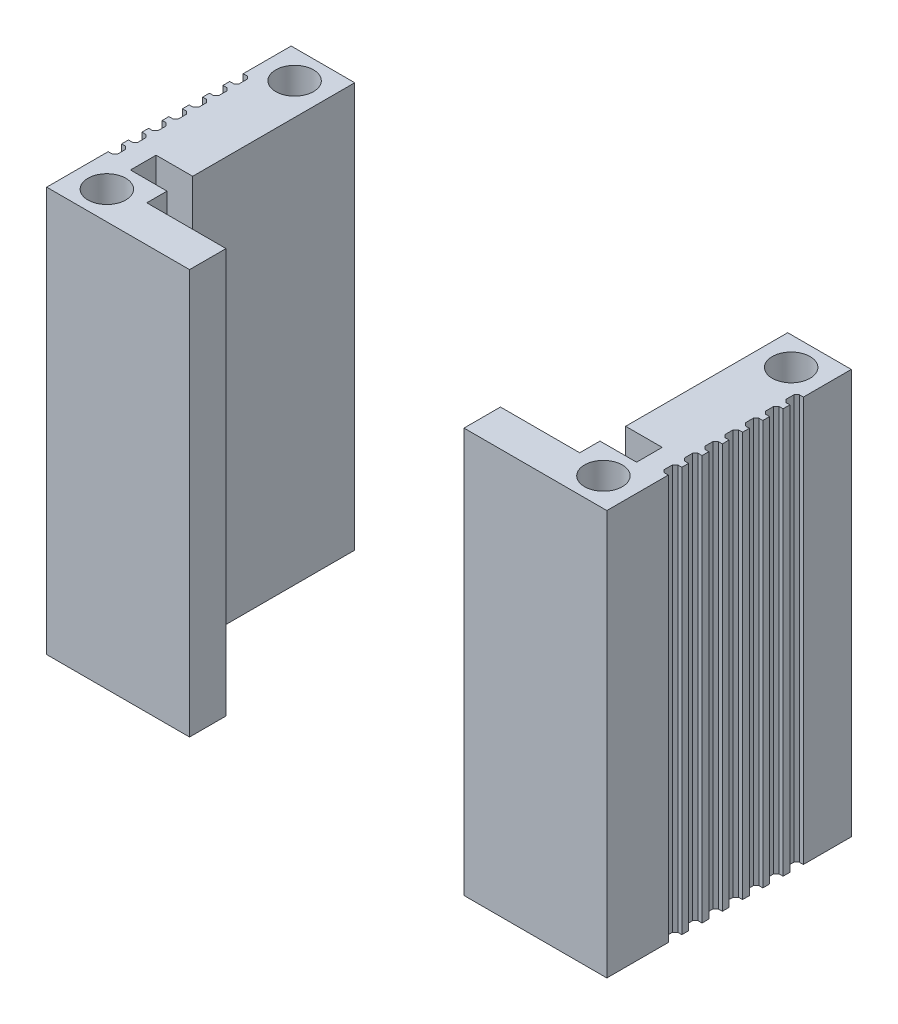
SolidWorks part; units mm, degrees
ref_plane "前视基准面" through (0, 0, 0) normal (0, 0, 1) x (1, 0, 0)
ref_plane "上视基准面" through (0, 0, 0) normal (0, 1, 0) x (1, 0, 0)
ref_plane "右视基准面" through (0, 0, 0) normal (1, 0, 0) x (0, 0, -1)
sketch "草图1" plane through (0, 0, 0) normal (0, 0, 1) x (1, 0, 0)
  line L4 (18.7373, -9.5383) -> (18.7373, 20.4363)
  line L5 (18.7373, 20.4363) -> (-18.7373, 20.4363)
  line L6 (-18.7373, 20.4363) -> (-18.7373, -9.5383)
  line L7 (-18.7373, -9.5383) -> (18.7373, -9.5383)
  line L8 (18.7373, -9.5383) -> (18.7373, 20.4363)
  line L9 (18.7373, 20.4363) -> (-18.7373, 20.4363)
  line L10 (-18.7373, 20.4363) -> (-18.7373, -9.5383)
  line L11 (-18.7373, -9.5383) -> (18.7373, -9.5383)
  dimension "D1" = 0
extrude "凸台-拉伸1" add sketch "草图1" along normal blind 3
sketch "草图2" plane through (-18.7373, 0, 0) normal (-1, 0, 0) x (0, 0, 1)
  line L4 (0, 20.4363) -> (0, -9.5383)
  line L5 (0, -9.5383) -> (3, -9.5383)
  line L6 (3, -9.5383) -> (3, 20.4363)
  line L7 (3, 20.4363) -> (0, 20.4363)
  line L8 (0, 20.4363) -> (0, -9.5383)
  line L9 (0, -9.5383) -> (3, -9.5383)
  line L10 (3, -9.5383) -> (3, 20.4363)
  line L11 (3, 20.4363) -> (0, 20.4363)
  dimension "D1" = 0
extrude "凸台-拉伸2" add sketch "草图2" along normal blind 3
sketch "草图3" plane through (18.7373, 0, 0) normal (1, 0, 0) x (0, 0, -1)
  line L4 (0, -9.5383) -> (0, 20.4363)
  line L5 (0, 20.4363) -> (-3, 20.4363)
  line L6 (-3, 20.4363) -> (-3, -9.5383)
  line L7 (-3, -9.5383) -> (0, -9.5383)
  line L8 (0, -9.5383) -> (0, 20.4363)
  line L9 (0, 20.4363) -> (-3, 20.4363)
  line L10 (-3, 20.4363) -> (-3, -9.5383)
  line L11 (-3, -9.5383) -> (0, -9.5383)
  dimension "D1" = 0
extrude "凸台-拉伸3" add sketch "草图3" along normal blind 3
sketch "草图4" plane through (0, 0, 0) normal (0, 0, -1) x (-1, 0, 0)
  line L0 (-18.7373, -9.5383) -> (-18.7373, 20.4363) construction
  line L1 (-18.7373, -9.5383) -> (-18.7373, 20.4363)
  line L2 (18.7373, 20.4363) -> (18.7373, -9.5383) construction
  line L3 (18.7373, 20.4363) -> (18.7373, -9.5383)
  line L4 (-18.7373, 20.4363) -> (-21.7373, 20.4363)
  line L5 (18.7373, -9.5383) -> (21.7373, -9.5383)
  line L8 (-21.7373, -9.5383) -> (21.7373, -9.5383)
  line L9 (-21.7373, 20.4363) -> (-21.7373, -9.5383)
  line L10 (21.7373, 20.4363) -> (-21.7373, 20.4363)
  line L11 (21.7373, -9.5383) -> (21.7373, 20.4363)
  line L12 (-21.7373, -9.5383) -> (-18.7373, -9.5383)
  line L13 (-21.7373, 20.4363) -> (-21.7373, -9.5383)
  line L14 (21.7373, 20.4363) -> (18.7373, 20.4363)
  line L15 (21.7373, -9.5383) -> (21.7373, 20.4363)
  dimension "D1" = 0
extrude "凸台-拉伸4" add sketch "草图4" along normal blind 1.6 contours L12 L1 L4 L13 | L14 L3 L5 L15
sketch "草图5" plane through (0, 0, -1.6) normal (0, 0, -1) x (-1, 0, 0)
  line L0 (-18.7373, -9.5383) -> (-16.0288, -9.5383)
  line L1 (18.7373, -9.5383) -> (-18.7373, -9.5383) construction
  line L2 (-16.0288, -9.5383) -> (-16.0288, 20.4363)
  line L3 (-18.7373, 20.4363) -> (-16.0288, 20.4363)
  line L4 (-21.7373, 20.4363) -> (-21.7373, -9.5383)
  line L5 (-21.7373, -9.5383) -> (-18.7373, -9.5383)
  line L6 (-18.7373, -9.5383) -> (-18.7373, 20.4363)
  line L7 (-18.7373, 20.4363) -> (-21.7373, 20.4363)
  line L8 (-21.7373, 20.4363) -> (-21.7373, -9.5383)
  line L9 (-21.7373, -9.5383) -> (-18.7373, -9.5383)
  line L11 (-18.7373, 20.4363) -> (-21.7373, 20.4363)
  line L12 (18.7373, 20.4363) -> (21.7373, 20.4363)
  line L22 (21.7373, -9.5383) -> (18.7373, -9.5383)
  line L23 (21.7373, 20.4363) -> (21.7373, -9.5383)
  line L24 (18.7373, 20.4363) -> (16.0288, 20.4363)
  line L25 (16.0288, -9.5383) -> (16.0288, 20.4363)
  line L26 (18.7373, -9.5383) -> (16.0288, -9.5383)
  dimension "D1" = 0
extrude "凸台-拉伸7" add sketch "草图5" along normal up to vertex (1.6 mm away) contours L8 L9 L0 L2 L3 L11 | L12 L23 L22 L26 L25 L24
sketch "草图7" plane through (0, 0, 0) normal (0, 0, -1) x (-1, 0, 0)
  line L4 (18.7373, -9.5383) -> (18.7373, 20.4363)
  line L5 (18.7373, 20.4363) -> (-18.7373, 20.4363)
  line L6 (-18.7373, 20.4363) -> (-18.7373, -9.5383)
  line L7 (-18.7373, -9.5383) -> (18.7373, -9.5383)
  line L8 (18.7373, -9.5383) -> (18.7373, 20.4363)
  line L9 (18.7373, 20.4363) -> (-18.7373, 20.4363)
  line L10 (-18.7373, 20.4363) -> (-18.7373, -9.5383)
  line L11 (-18.7373, -9.5383) -> (18.7373, -9.5383)
  dimension "D1" = 0
extrude "切除-拉伸1" cut sketch "草图7" against normal blind 0.3
sketch "草图8" plane through (0, 0, 3) normal (0, 0, 1) x (1, 0, 0)
  line L1 (-10.16, 19.648) -> (-10.16, 17.408) construction
  line L2 (-10.16, 20.4363) -> (-10.16, -9.5383)
  line L3 (10.16, 17.408) -> (10.16, 19.648) construction
  line L4 (-21.7373, -9.5383) -> (21.7373, -9.5383)
  line L5 (21.7373, -9.5383) -> (21.7373, 20.4363)
  line L6 (21.7373, 20.4363) -> (-21.7373, 20.4363)
  line L7 (-21.7373, 20.4363) -> (-21.7373, -9.5383)
  line L8 (-10.16, -9.5383) -> (10.16, -9.5383)
  line L10 (10.16, 20.4363) -> (-10.16, 20.4363)
  line L12 (10.16, -9.5383) -> (10.16, 20.4363)
  dimension "D1" = 0
extrude "切除-拉伸3" cut sketch "草图8" against normal up to surface (2.7 mm away) contours L8 L12 L10 L2 up to face at (0, 5.449, 0.3)
sketch "草图9" plane through (0, 0, 0.3) normal (0, 0, -1) x (-1, 0, 0)
  line L0 (16.0288, -9.5383) -> (16.0288, 20.4363) construction
  line L1 (16.0288, -9.5383) -> (16.0288, 20.4363)
  line L2 (-16.0288, -9.5383) -> (-16.0288, 20.4363) construction
  line L3 (-16.0288, -9.5383) -> (-16.0288, 20.4363)
  line L8 (10.16, 20.4363) -> (10.16, -9.5383)
  line L9 (10.16, -9.5383) -> (18.7373, -9.5383)
  line L10 (18.7373, -9.5383) -> (18.7373, 20.4363)
  line L11 (18.7373, 20.4363) -> (10.16, 20.4363)
  line L12 (10.16, 20.4363) -> (10.16, -9.5383)
  line L13 (10.16, -9.5383) -> (16.0288, -9.5383)
  line L15 (16.0288, 20.4363) -> (10.16, 20.4363)
  line L16 (-10.16, -9.5383) -> (-10.16, 20.4363)
  line L17 (-10.16, 20.4363) -> (-18.7373, 20.4363)
  line L18 (-18.7373, 20.4363) -> (-18.7373, -9.5383)
  line L19 (-18.7373, -9.5383) -> (-10.16, -9.5383)
  line L20 (-10.16, -9.5383) -> (-10.16, 20.4363)
  line L21 (-10.16, 20.4363) -> (-16.0288, 20.4363)
  line L23 (-16.0288, -9.5383) -> (-10.16, -9.5383)
  dimension "D1" = 0
  dimension "D2" = 0
extrude "切除-拉伸4" cut sketch "草图9" against normal blind 1.5
sketch "草图10" plane through (0, 0, 3) normal (0, 0, 1) x (1, 0, 0)
  line L4 (-10.16, -9.5383) -> (-10.16, 20.4363)
  line L5 (-10.16, 20.4363) -> (-21.7373, 20.4363)
  line L6 (-21.7373, 20.4363) -> (-21.7373, -9.5383)
  line L7 (-21.7373, -9.5383) -> (-10.16, -9.5383)
  line L8 (-10.16, -9.5383) -> (-10.16, 20.4363)
  line L9 (-10.16, 20.4363) -> (-21.7373, 20.4363)
  line L10 (-21.7373, 20.4363) -> (-21.7373, -9.5383)
  line L11 (-21.7373, -9.5383) -> (-10.16, -9.5383)
  line L12 (10.16, 20.4363) -> (10.16, -9.5383)
  line L13 (10.16, -9.5383) -> (21.7373, -9.5383)
  line L14 (21.7373, -9.5383) -> (21.7373, 20.4363)
  line L15 (21.7373, 20.4363) -> (10.16, 20.4363)
  line L16 (10.16, 20.4363) -> (10.16, -9.5383)
  line L17 (10.16, -9.5383) -> (21.7373, -9.5383)
  line L18 (21.7373, -9.5383) -> (21.7373, 20.4363)
  line L19 (21.7373, 20.4363) -> (10.16, 20.4363)
  dimension "D1" = 0
  dimension "D2" = 0
extrude "凸台-拉伸8" add sketch "草图10" along normal blind 1.5
sketch "草图11" plane through (21.7373, 0, 0) normal (1, 0, 0) x (0, 0, -1)
  line L4 (-4.5, -9.5383) -> (13.6, -9.5383)
  line L5 (13.6, -9.5383) -> (13.6, 20.4363)
  line L6 (13.6, 20.4363) -> (-4.5, 20.4363)
  line L7 (-4.5, 20.4363) -> (-4.5, -9.5383)
  line L8 (-4.5, -9.5383) -> (13.6, -9.5383)
  line L9 (13.6, -9.5383) -> (13.6, 20.4363)
  line L10 (13.6, 20.4363) -> (-4.5, 20.4363)
  line L11 (-4.5, 20.4363) -> (-4.5, -9.5383)
  dimension "D1" = 0
extrude "切除-拉伸5" cut sketch "草图11" against normal blind 1
sketch "草图12" plane through (-21.7373, 0, 0) normal (-1, 0, 0) x (0, 0, 1)
  line L4 (4.5, 20.4363) -> (-13.6, 20.4363)
  line L5 (-13.6, 20.4363) -> (-13.6, -9.5383)
  line L6 (-13.6, -9.5383) -> (4.5, -9.5383)
  line L7 (4.5, -9.5383) -> (4.5, 20.4363)
  line L8 (4.5, 20.4363) -> (-13.6, 20.4363)
  line L9 (-13.6, 20.4363) -> (-13.6, -9.5383)
  line L10 (-13.6, -9.5383) -> (4.5, -9.5383)
  line L11 (4.5, -9.5383) -> (4.5, 20.4363)
  dimension "D1" = 0
extrude "切除-拉伸6" cut sketch "草图12" against normal blind 1
sketch "草图14" plane through (0, -9.5383, 0) normal (0, -1, 0) x (1, 0, 0)
  circle A0 centre (18.3831, -11.5) radius 1.4 construction
  circle A1 centre (18.3831, -11.5) radius 1.4
  circle A2 centre (18.3831, 2.4) radius 1.4 construction
  circle A3 centre (18.3831, 2.4) radius 1.4
  circle A4 centre (-18.3831, 2.4) radius 1.4 construction
  circle A5 centre (-18.3831, 2.4) radius 1.4
  circle A6 centre (-18.3831, -11.5) radius 1.4 construction
  circle A7 centre (-18.3831, -11.5) radius 1.4
extrude "切除-拉伸7" cut sketch "草图14" against normal up to next
sketch "草图16" plane through (0, -9.5383, 0) normal (0, -1, 0) x (1, 0, 0)
  line L0 (-20.7373, -4.55) -> (-20.2373, -4.55)
  line L1 (-20.7373, -13.6) -> (-20.7373, 4.5) construction
  line L2 (-20.7373, -6.05) -> (-20.2373, -6.05)
  line L3 (-20.7373, -4.55) -> (-20.7373, -5.55)
  line L4 (-20.7373, -5.55) -> (-20.2373, -5.55)
  line L5 (-20.7373, -6.05) -> (-20.7373, -7.05)
  line L6 (-20.7373, -5.55) -> (-20.2373, -5.55)
  line L7 (-20.2373, -5.55) -> (-20.2373, -4.55)
  line L8 (-20.7373, -7.05) -> (-20.2373, -7.05)
  line L9 (-20.7373, -7.05) -> (-20.2373, -7.05)
  line L10 (-20.2373, -7.05) -> (-20.2373, -6.05)
  line L11 (-20.7373, -7.55) -> (-20.2373, -7.55)
  line L12 (-20.7373, -7.55) -> (-20.7373, -8.55)
  line L13 (-20.7373, -8.55) -> (-20.2373, -8.55)
  line L14 (-20.7373, -8.55) -> (-20.2373, -8.55)
  line L15 (-20.2373, -8.55) -> (-20.2373, -7.55)
  line L16 (-20.7373, -9.05) -> (-20.2373, -9.05)
  line L17 (-20.7373, -9.05) -> (-20.7373, -10.05)
  line L18 (-20.7373, -10.05) -> (-20.2373, -10.05)
  line L19 (-20.7373, -10.05) -> (-20.2373, -10.05)
  line L20 (-20.2373, -10.05) -> (-20.2373, -9.05)
  line L21 (-20.7373, -3.05) -> (-20.2373, -3.05)
  line L22 (-20.7373, -3.05) -> (-20.7373, -4.05)
  line L23 (-20.7373, -4.05) -> (-20.2373, -4.05)
  line L24 (-20.7373, -4.05) -> (-20.2373, -4.05)
  line L25 (-20.2373, -4.05) -> (-20.2373, -3.05)
  line L26 (-20.7373, -1.55) -> (-20.2373, -1.55)
  line L27 (-20.7373, -1.55) -> (-20.7373, -2.55)
  line L28 (-20.7373, -2.55) -> (-20.2373, -2.55)
  line L29 (-20.7373, -2.55) -> (-20.2373, -2.55)
  line L30 (-20.2373, -2.55) -> (-20.2373, -1.55)
  line L31 (-20.7373, -0.05) -> (-20.2373, -0.05)
  line L32 (-20.7373, -0.05) -> (-20.7373, -1.05)
  line L33 (-20.7373, -1.05) -> (-20.2373, -1.05)
  line L34 (-20.7373, -1.05) -> (-20.2373, -1.05)
  line L35 (-20.2373, -1.05) -> (-20.2373, -0.05)
  line L38 (20.2373, -1.05) -> (20.2373, -0.05)
  line L39 (20.7373, -1.05) -> (20.2373, -1.05)
  line L40 (20.7373, -1.05) -> (20.2373, -1.05)
  line L41 (20.7373, -0.05) -> (20.7373, -1.05)
  line L42 (20.7373, -0.05) -> (20.2373, -0.05)
  line L43 (20.2373, -2.55) -> (20.2373, -1.55)
  line L44 (20.7373, -2.55) -> (20.2373, -2.55)
  line L45 (20.7373, -2.55) -> (20.2373, -2.55)
  line L46 (20.7373, -1.55) -> (20.7373, -2.55)
  line L47 (20.7373, -1.55) -> (20.2373, -1.55)
  line L48 (20.2373, -4.05) -> (20.2373, -3.05)
  line L49 (20.7373, -4.05) -> (20.2373, -4.05)
  line L50 (20.7373, -4.05) -> (20.2373, -4.05)
  line L51 (20.7373, -3.05) -> (20.7373, -4.05)
  line L52 (20.7373, -3.05) -> (20.2373, -3.05)
  line L53 (20.2373, -10.05) -> (20.2373, -9.05)
  line L54 (20.7373, -10.05) -> (20.2373, -10.05)
  line L55 (20.7373, -10.05) -> (20.2373, -10.05)
  line L56 (20.7373, -9.05) -> (20.7373, -10.05)
  line L57 (20.7373, -9.05) -> (20.2373, -9.05)
  line L58 (20.2373, -8.55) -> (20.2373, -7.55)
  line L59 (20.7373, -8.55) -> (20.2373, -8.55)
  line L60 (20.7373, -8.55) -> (20.2373, -8.55)
  line L61 (20.7373, -7.55) -> (20.7373, -8.55)
  line L62 (20.7373, -7.55) -> (20.2373, -7.55)
  line L63 (20.2373, -7.05) -> (20.2373, -6.05)
  line L64 (20.7373, -7.05) -> (20.2373, -7.05)
  line L65 (20.7373, -7.05) -> (20.2373, -7.05)
  line L66 (20.2373, -5.55) -> (20.2373, -4.55)
  line L67 (20.7373, -5.55) -> (20.2373, -5.55)
  line L68 (20.7373, -6.05) -> (20.7373, -7.05)
  line L69 (20.7373, -5.55) -> (20.2373, -5.55)
  line L70 (20.7373, -4.55) -> (20.7373, -5.55)
  line L71 (20.7373, -6.05) -> (20.2373, -6.05)
  line L72 (20.7373, -4.55) -> (20.2373, -4.55)
  line M5 (-20.7373, 4.5) -> (-20.7373, -13.6)
extrude "切除-拉伸8" cut sketch "草图16" against normal up to next contours L56 L57 L53 L54 | L61 L62 L58 L59 | L68 L71 L63 L64 | L70 L72 L66 L67 | L51 L52 L48 L49 | L46 L47 L43 L44 | L41 L42 L38 L39 | L18 L20 L16 M5 | L13 L15 L11 M5 | L8 L10 L2 M5 | L4 L7 L0 M5 | L33 L35 L31 M5 | L28 L30 L26 M5 | L23 L25 L21 M5
chamfer "倒角1" distance 0.2 angle 45 14 edges at (20.2373, 5.449, -1.05) (20.2373, 5.449, -2.55) (20.2373, 5.449, -4.05) (20.2373, 5.449, -5.55) (20.2373, 5.449, -7.05) (20.2373, 5.449, -0.05) (20.2373, 5.449, -1.55) (20.2373, 5.449, -3.05) (20.2373, 5.449, -4.55) (20.2373, 5.449, -6.05) (20.2373, 5.449, -7.55) (20.2373, 5.449, -8.55) (20.2373, 5.449, -9.05) (20.2373, 5.449, -10.05)
chamfer "倒角2" distance 0.2 angle 45 14 edges at (-20.2373, 5.449, -9.05) (-20.2373, 5.449, -7.55) (-20.2373, 5.449, -6.05) (-20.2373, 5.449, -4.55) (-20.2373, 5.449, -3.05) (-20.2373, 5.449, -1.55) (-20.2373, 5.449, -0.05) (-20.2373, 5.449, -1.05) (-20.2373, 5.449, -2.55) (-20.2373, 5.449, -4.05) (-20.2373, 5.449, -5.55) (-20.2373, 5.449, -7.05) (-20.2373, 5.449, -8.55) (-20.2373, 5.449, -10.05)
